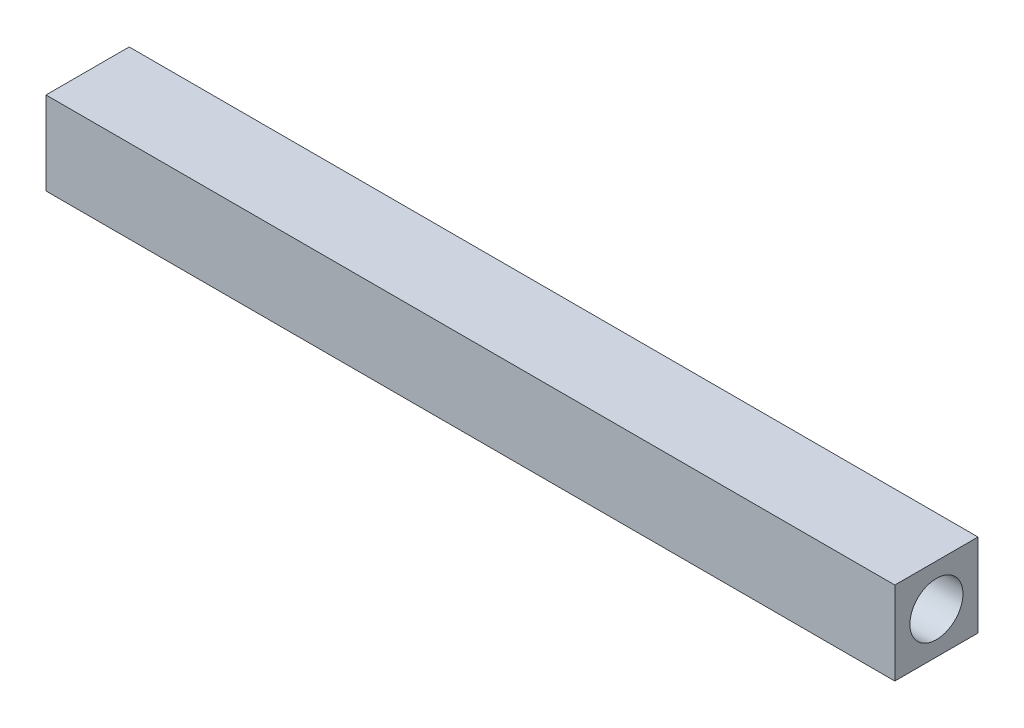
SolidWorks part; units mm, degrees
material "Hexcel AS4C (3000 Filaments)"
ref_plane "Front Plane" through (0, 0, 0) normal (0, 0, 1) x (1, 0, 0)
ref_plane "Top Plane" through (0, 0, 0) normal (0, 1, 0) x (1, 0, 0)
ref_plane "Right Plane" through (0, 0, 0) normal (1, 0, 0) x (0, 0, -1)
sketch "Sketch1" plane through (0, 0, 0) normal (1, 0, 0) x (0, 0, -1)
  line L1 (-2.4892, -2.4892) -> (2.4892, -2.4892)
  line L2 (-2.4892, -2.4892) -> (-2.4892, 2.4892)
  line L3 (-2.4892, 2.4892) -> (2.4892, 2.4892)
  line L4 (2.4892, -2.4892) -> (2.4892, 2.4892)
  line L5 (-2.4892, -2.4892) -> (2.4892, 2.4892) construction
  line L6 (-2.4892, 2.4892) -> (2.4892, -2.4892) construction
  circle A0 centre (0, 0) radius 1.5875
  point P0 (0, 0)
  dimension "D3" = 3.175
  dimension "D1" = 4.9784
  dimension "D2" = 4.9784
extrude "Boss-Extrude1" add sketch "Sketch1" along normal blind 50.8
